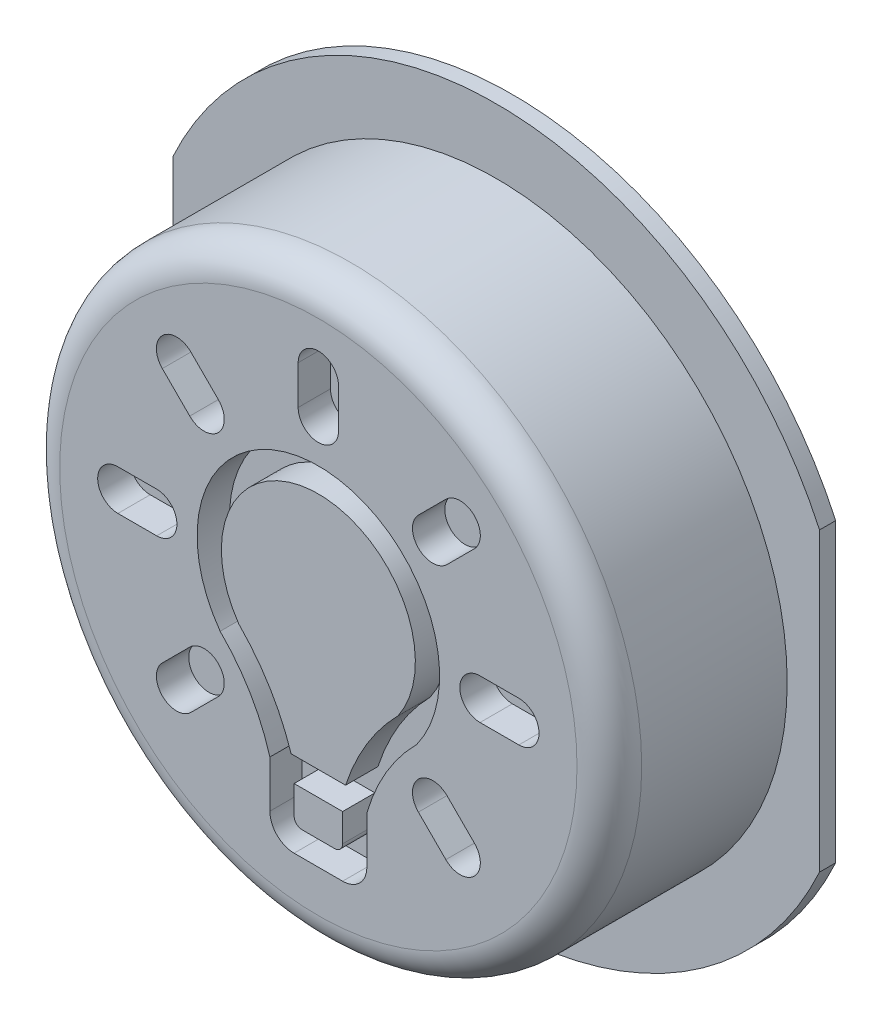
SolidWorks part; units mm, degrees
ref_plane "Plano frontal" through (0, 0, 0) normal (0, 0, 1) x (1, 0, 0)
ref_plane "Plano superior" through (0, 0, 0) normal (0, 1, 0) x (1, 0, 0)
ref_plane "Plano direito" through (0, 0, 0) normal (1, 0, 0) x (0, 0, -1)
sketch "Esboço1" plane through (0, 0, 0) normal (0, 0, 1) x (1, 0, 0)
  circle A0 centre (0, 0) radius 9
  dimension "D1" = 18
extrude "Ressalto-extrusão1" add sketch "Esboço1" along normal blind 6
fillet "Filete1" radius 1 1 edges at (9, 0, 6)
shell "Casca1" thickness 2
sketch "Esboço2" plane through (0, 0, 4) normal (0, 0, -1) x (-1, 0, 0)
  line L1 (-2.175, -2.175) -> (2.175, -2.175)
  line L2 (-2.175, -2.175) -> (-2.175, 2.175)
  line L3 (-2.175, 2.175) -> (2.175, 2.175)
  line L4 (2.175, -2.175) -> (2.175, 2.175)
  line L5 (-2.175, -2.175) -> (2.175, 2.175) construction
  line L6 (-2.175, 2.175) -> (2.175, -2.175) construction
  line L7 (-4.175, -4.175) -> (4.175, -4.175)
  line L8 (-4.175, -4.175) -> (-4.175, 4.175)
  line L9 (-4.175, 4.175) -> (4.175, 4.175)
  line L10 (4.175, -4.175) -> (4.175, 4.175)
  line L11 (-4.175, -4.175) -> (4.175, 4.175) construction
  line L12 (-4.175, 4.175) -> (4.175, -4.175) construction
  point P0 (0, 0)
  point P6 (0, 0)
  dimension "D1" = 4.35
  dimension "D2" = 4.35
  dimension "D3" = 2
  dimension "D4" = 2
extrude "Ressalto-extrusão2" add sketch "Esboço2" along normal blind 4
fillet "Filete2" radius 1 4 edges at (-4.175, 4.175, 2) (-4.175, -4.175, 2) (4.175, -4.175, 2) (4.175, 4.175, 2)
sketch "Esboço4" plane through (0, 0, 6) normal (0, 0, 1) x (1, 0, 0)
  line L0 (37.5, 112.5) -> (187.5, 112.5) construction
  line L1 (37.5, 112.5) -> (190.4007, 112.5) construction
  line L15 (-0.625, 6.5) -> (-0.625, 5.3)
  line L17 (-1.5, -4.5) -> (-1.5, -5.95)
  line L18 (-0.75, -6.7) -> (0.75, -6.7)
  line L19 (1.5, -4.5) -> (1.5, -5.95)
  line L20 (0.625, 6.5) -> (0.625, 5.3)
  line L21 (3.9421, 5.126) -> (3.0936, 4.2775)
  line L66 (4.826, 4.2421) -> (3.9775, 3.3936)
  line L67 (6.2, 0.925) -> (5, 0.925)
  line L68 (6.2, -0.325) -> (5, -0.325)
  line L69 (4.826, -3.6421) -> (3.9775, -2.7936)
  line L70 (3.9421, -4.526) -> (3.0936, -3.6775)
  line L73 (-3.9421, -4.526) -> (-3.0936, -3.6775)
  line L74 (-4.826, -3.6421) -> (-3.9775, -2.7936)
  line L75 (-6.2, -0.325) -> (-5, -0.325)
  line L76 (-6.2, 0.925) -> (-5, 0.925)
  line L77 (-4.826, 4.2421) -> (-3.9775, 3.3936)
  line L78 (-3.9421, 5.126) -> (-3.0936, 4.2775)
  line L79 (0.625, -5.9) -> (0.625, -4.7) [skipped]
  line L80 (-0.625, -5.9) -> (-0.625, -4.7) [skipped]
  line L81 (0, 8) -> (0, -8) construction
  line L82 (-0.8428, -4.0841) -> (0.8428, -4.0841)
  line L83 (-0.75, -4.8341) -> (0.75, -4.8341)
  line L84 (-0.75, -4.8341) -> (-0.75, -5.7)
  line L85 (-0.5, -5.95) -> (0.5, -5.95)
  line L86 (0.75, -4.8341) -> (0.75, -5.7)
  arc A321 (2.4616, -1.4148) -> (-2.4616, -1.4148) centre (0, 0.3) ccw
  arc A324 (-0.625, 5.3) -> (0.625, 5.3) centre (0, 5.3) ccw
  arc A325 (0.625, 6.5) -> (-0.625, 6.5) centre (0, 6.5) ccw
  arc A326 (3.0936, 4.2775) -> (3.9775, 3.3936) centre (3.5355, 3.8355) ccw
  arc A327 (4.826, 4.2421) -> (3.9421, 5.126) centre (4.3841, 4.6841) ccw
  arc A328 (5, 0.925) -> (5, -0.325) centre (5, 0.3) ccw
  arc A329 (6.2, -0.325) -> (6.2, 0.925) centre (6.2, 0.3) ccw
  arc A333 (3.9775, -2.7936) -> (3.0936, -3.6775) centre (3.5355, -3.2355) ccw
  arc A334 (3.9421, -4.526) -> (4.826, -3.6421) centre (4.3841, -4.0841) ccw
  arc A337 (-3.0936, -3.6775) -> (-3.9775, -2.7936) centre (-3.5355, -3.2355) ccw
  arc A338 (-4.826, -3.6421) -> (-3.9421, -4.526) centre (-4.3841, -4.0841) ccw
  arc A339 (-5, -0.325) -> (-5, 0.925) centre (-5, 0.3) ccw
  arc A340 (-6.2, 0.925) -> (-6.2, -0.325) centre (-6.2, 0.3) ccw
  arc A341 (-3.9775, 3.3936) -> (-3.0936, 4.2775) centre (-3.5355, 3.8355) ccw
  arc A342 (-3.9421, 5.126) -> (-4.826, 4.2421) centre (-4.3841, 4.6841) ccw
  arc A343 (0.625, -4.7) -> (-0.625, -4.7) centre (0, -4.7) ccw [skipped]
  arc A344 (-0.625, -5.9) -> (0.625, -5.9) centre (0, -5.9) ccw [skipped]
  arc A345 (-1.5, -4.5) -> (-3.0369, -1.9) centre (-7.2673, -6.1548) ccw
  circle A346 centre (0, 0) radius 8 construction
  arc A347 (1.5, -4.5) -> (3.0369, -1.9) centre (7.2673, -6.1548) cw
  arc A348 (3.0369, -1.9) -> (-3.0369, -1.9) centre (0, 0.3) ccw
  arc A349 (0.75, -6.7) -> (1.5, -5.95) centre (0.75, -5.95) ccw
  arc A350 (-1.5, -5.95) -> (-0.75, -6.7) centre (-0.75, -5.95) ccw
  arc A351 (0.5, -5.95) -> (0.75, -5.7) centre (0.5, -5.7) ccw
  arc A352 (-0.75, -5.7) -> (-0.5, -5.95) centre (-0.5, -5.7) ccw
  arc A353 (-0.8428, -4.0841) -> (-2.4616, -1.4148) centre (-7.2673, -6.1548) ccw
  arc A354 (0.8428, -4.0841) -> (2.4616, -1.4148) centre (7.2673, -6.1548) cw
  arc A355 (-0.7791, -4.2931) -> (-2.5081, -1.3681) centre (-7.2673, -6.1548) ccw construction
  arc A356 (0.7791, -4.2931) -> (2.5081, -1.3681) centre (7.2673, -6.1548) cw construction
  point P62 (0, 0.3)
  point P63 (1.5, -6.7)
  dimension "D2" = 0.75
  dimension "D7" = 0.75
  dimension "D8" = 1.25
  dimension "D9" = 1.25
  dimension "D10" = 1.2
  dimension "D13" = 8
  dimension "D5" = 0.3
  dimension "D15" = 2.2
  dimension "D12" = 0
  dimension "D14" = 0.3
  dimension "D1" = 6
  dimension "D3" = 1.5
  dimension "D11" = 5
  dimension "D16" = 6
  dimension "D4" = 0.25
  dimension "D6" = 7
  dimension "D17" = 2.2
  dimension "D18" = 0.75
  dimension "D19" = 0.75
extrude "Corte-extrusão2" cut sketch "Esboço4" against normal blind 1
sketch "Esboço6" plane through (0, 0, 0) normal (0, 0, -1) x (-1, 0, 0)
  circle A0 centre (0, 0) radius 9
  circle A1 centre (0, 0) radius 11
  dimension "D1" = 2
extrude "Ressalto-extrusão3" add sketch "Esboço6" against normal blind 0.5
sketch "Esboço7" plane through (0, 0, 0) normal (0, 0, -1) x (-1, 0, 0)
  line L0 (-10, 4.5826) -> (-10, -4.5826)
  line L1 (10, 4.5826) -> (10, -4.5826)
  arc A0 (-10, 4.5826) -> (-10, -4.5826) centre (0, 0) ccw
  arc A1 (10, -4.5826) -> (10, 4.5826) centre (0, 0) ccw
  circle A2 centre (0, 0) radius 11 construction
  dimension "D3" = 0
  dimension "D1" = 10
  dimension "D2" = 10
extrude "Corte-extrusão4" cut sketch "Esboço7" against normal through all
sketch "Esboço8" plane through (0, 0, 4) normal (0, 0, -1) x (-1, 0, 0)
  line L1 (-2.175, -2.175) -> (2.175, -2.175)
  line L2 (-2.175, -2.175) -> (-2.175, 2.175)
  line L3 (-2.175, 2.175) -> (2.175, 2.175)
  line L4 (2.175, -2.175) -> (2.175, 2.175)
extrude "Ressalto-extrusão4" add sketch "Esboço8" along normal blind 2
